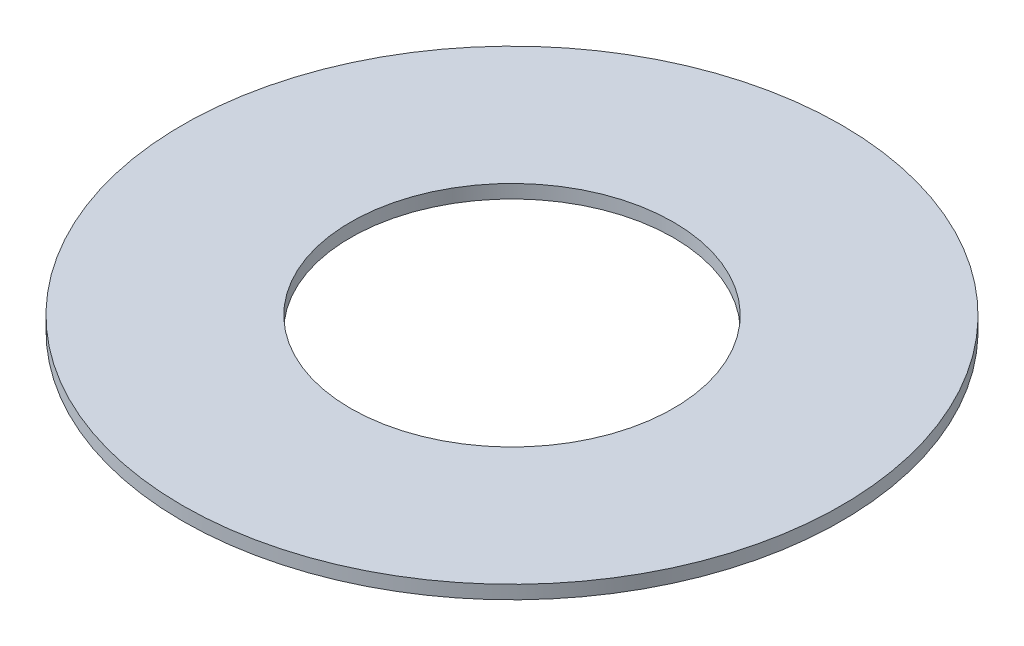
SolidWorks part; units mm, degrees
ref_plane "Front Plane" through (0, 0, 0) normal (0, 0, 1) x (1, 0, 0)
ref_plane "Top Plane" through (0, 0, 0) normal (0, 1, 0) x (1, 0, 0)
ref_plane "Right Plane" through (0, 0, 0) normal (1, 0, 0) x (0, 0, -1)
sketch "Sketch1" plane through (0, 0, 0) normal (0, 1, 0) x (1, 0, 0)
  circle A0 centre (0, 0) radius 12.25
  circle A1 centre (0, 0) radius 6
  dimension "D1" = 12
  dimension "D2" = 24.5
extrude "Boss-Extrude1" add sketch "Sketch1" along normal blind 0.5
sketch "Sketch2" plane through (0, 0, 0) normal (0, 0, 1) x (1, 0, 0)
  line L0 (0, 0) -> (0, 6.915) construction
